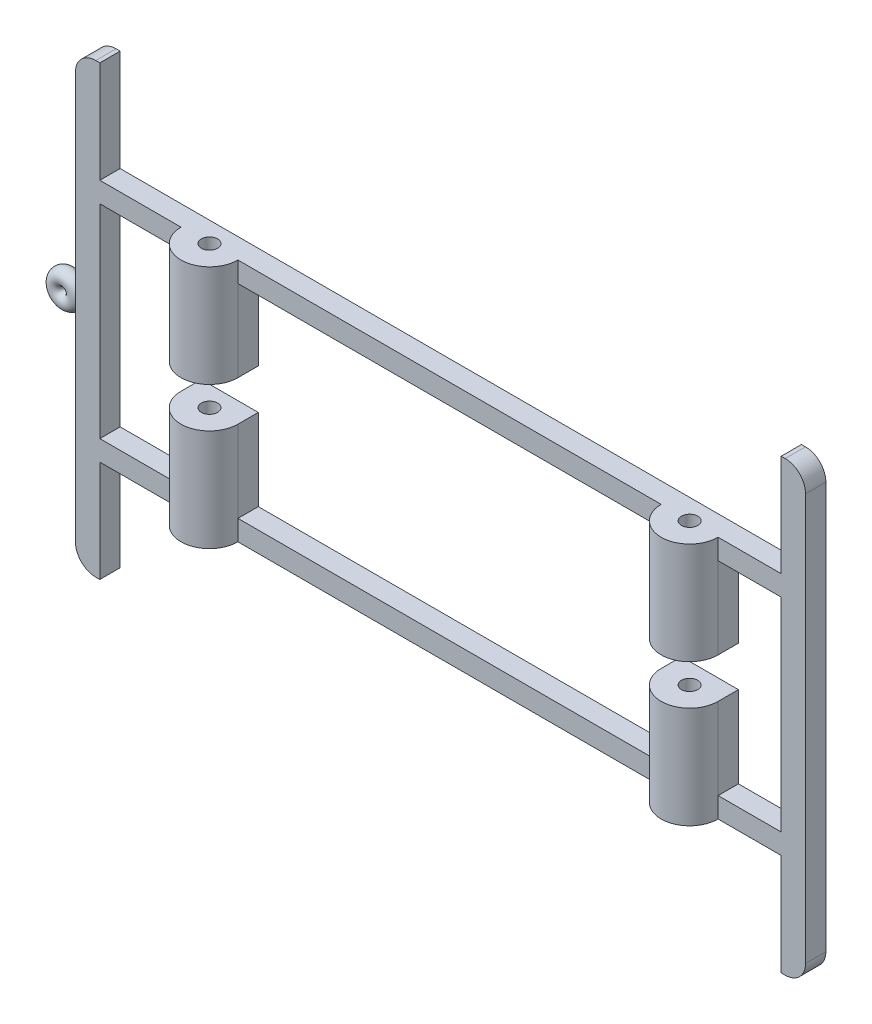
SolidWorks part; units mm, degrees
ref_plane "Front Plane" through (0, 0, 0) normal (0, 0, 1) x (1, 0, 0)
ref_plane "Top Plane" through (0, 0, 0) normal (0, 1, 0) x (1, 0, 0)
ref_plane "Right Plane" through (0, 0, 0) normal (1, 0, 0) x (0, 0, -1)
sketch "Sketch1" plane through (0, 0, 0) normal (0, 0, 1) x (1, 0, 0)
  line L0 (-83.75, -25) -> (83.75, -25)
  line L1 (-83.75, -30) -> (83.75, -30)
  line L2 (-83.75, -30) -> (-83.75, 30)
  line L3 (-83.75, 30) -> (83.75, 30)
  line L4 (83.75, -30) -> (83.75, -25)
  line L5 (-83.75, -30) -> (-69.7917, -25) construction
  line L6 (-83.75, 30) -> (-69.7917, 25) construction
  line L7 (0, 0) -> (0, 22.6691)
  line L8 (-78.75, 25) -> (83.75, 25)
  line L9 (83.75, -55) -> (83.75, -30)
  line L10 (-78.75, 25) -> (-83.75, 25)
  line L11 (-78.75, -25) -> (78.75, -25) construction
  line L12 (-78.75, 25) -> (78.75, 25) construction
  line L13 (-78.75, -25) -> (-78.75, 25) construction
  line L14 (78.75, -25) -> (78.75, 25) construction
  line L15 (89.746, -55) -> (83.75, -55)
  line L16 (89.746, -65) -> (83.75, -65)
  line L17 (83.75, 55) -> (89.746, 55)
  line L18 (83.75, 25) -> (83.75, 30)
  line L19 (-83.75, 55) -> (-89.746, 55)
  line L20 (-89.746, -55) -> (-83.75, -55)
  line L21 (-83.75, -55) -> (-83.75, -30)
  line L22 (-89.746, 55) -> (-89.746, -55)
  line L23 (-83.75, 30) -> (-83.75, 55)
  line L24 (83.75, -30) -> (83.75, 30) construction
  line L25 (69.7917, 25) -> (83.75, 30) construction
  line L26 (69.7917, -25) -> (83.75, -30) construction
  line L27 (89.746, 55) -> (89.746, -55)
  line L28 (83.75, 30) -> (83.75, 55)
  line L29 (83.75, -30) -> (83.75, 30)
  point P0 (0, 0)
  dimension "D2" = 167.5
  dimension "D3" = 5
extrude "Boss-Extrude1" add sketch "Sketch1" along normal blind 5
sketch "Sketch2" plane through (0, 30, 0) normal (0, 1, 0) x (1, 0, 0)
  line L0 (-83.75, -5) -> (-56.79, -5)
  line L1 (-83.75, -5) -> (83.75, -5) construction
  line L2 (-63.79, -5) -> (-63.79, 0)
  line L3 (-83.75, 0) -> (83.75, 0) construction
  line L4 (-63.79, 0) -> (-49.79, 0)
  line L5 (-49.79, 0) -> (-49.79, -5)
  arc A0 (-63.79, -5) -> (-49.79, -5) centre (-56.79, -5) ccw
  line M2 (83.75, 0) -> (-83.75, 0)
  line M4 (-83.75, -5) -> (83.75, -5)
  dimension "D2" = 7
  dimension "D1" = 26.96
extrude "Boss-Extrude2" add sketch "Sketch2" against normal up to surface (60 mm away) contours L0 A0 M4 | L5 L2 L0 M2 M4 up to face at (0, -30, 2.5)
sketch "Sketch3" plane through (0, 30, 0) normal (0, 1, 0) x (1, 0, 0)
  circle A0 centre (-56.79, -5) radius 2
  dimension "D1" = 4
extrude "Cut-Extrude1" cut sketch "Sketch3" against normal through all
sketch "Sketch4" plane through (0, 30, 0) normal (0, 1, 0) x (1, 0, 0)
  line L2 (-49.79, -5) -> (83.75, -5) construction
  line L3 (68.25, 0) -> (68.25, -5)
  line L4 (-83.75, 0) -> (83.75, 0) construction
  line L5 (54.25, 0) -> (68.25, 0)
  line L6 (54.25, 0) -> (54.25, -5)
  arc A0 (54.25, -5) -> (68.25, -5) centre (61.25, -5) ccw
  dimension "D2" = 14
sketch "Sketch6" plane through (0, 0, 0) normal (0, 1, 0) x (1, 0, 0)
  line L1 (-94.746, 0) -> (-94.746, -3.8943) construction
  line L2 (-94.746, 0) -> (-97.246, 0) construction
  circle A0 centre (-97.246, -1.9471) radius 1.9471
  dimension "D2" = 2.5
revolve "Revolve2" add sketch "Sketch6" angle 360 about L1
sketch "Sketch9" plane through (0, 0, 0) normal (0, 1, 0) x (1, 0, 0)
  line L0 (-92.246, 0) -> (-89.746, 0)
  line L1 (-89.746, 0) -> (-89.746, -5)
  line L2 (-89.746, -5) -> (-92.246, 0)
extrude "Boss-Extrude7" add sketch "Sketch9" along normal mid plane 5
extrude "Boss-Extrude9" add sketch "Sketch4" against normal up to surface (60 mm away) up to face at (-56.79, -30, 7)
sketch "Sketch10" plane through (0, 30, 0) normal (0, 1, 0) x (1, 0, 0)
  circle A0 centre (61.25, -5) radius 2
  dimension "D1" = 4
extrude "Cut-Extrude3" cut sketch "Sketch10" against normal through all
fillet "Fillet2" radius 5 4 edges at (89.746, -55, 2.5) (89.746, 55, 2.5) (-89.746, 55, 2.5) (-89.746, -55, 2.5)
sketch "Sketch11" plane through (0, 0, 0) normal (0, 0, -1) x (-1, 0, 0)
  line L0 (-68.25, 4.9439) -> (-68.25, -4.9439)
  line L3 (-68.25, -25) -> (-68.25, 25) construction
  line L4 (63.79, 4.9439) -> (-68.25, 4.9439)
  line L5 (63.79, 4.9439) -> (63.79, -4.9439)
  line L6 (63.79, -4.9439) -> (-68.25, -4.9439)
  point P6 (0, 0)
extrude "Cut-Extrude5" cut sketch "Sketch11" against normal blind 36
